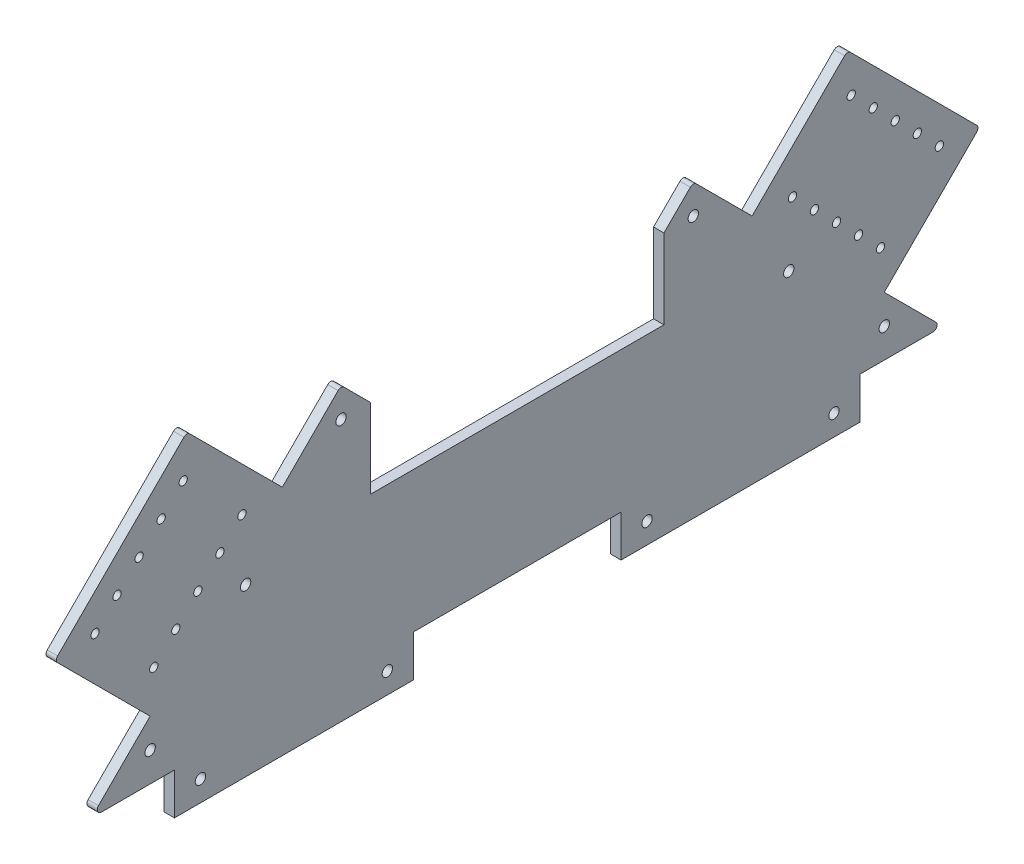
SolidWorks part; units mm, degrees
ref_plane "前视基准面" through (0, 0, 0) normal (0, 0, 1) x (1, 0, 0)
ref_plane "上视基准面" through (0, 0, 0) normal (0, 1, 0) x (1, 0, 0)
ref_plane "右视基准面" through (0, 0, 0) normal (1, 0, 0) x (0, 0, -1)
sketch "草图1" plane through (0, 0, 0) normal (1, 0, 0) x (0, 0, -1)
  line L0 (0, 207.0211) -> (0, -61.86) construction
  line L1 (205, 0) -> (-205, 0)
  line L2 (-205, 0) -> (-176.7157, 28.2843)
  line L4 (205, 0) -> (176.7157, 28.2843)
  line L5 (-84.7918, 120.2082) -> (-70.6497, 106.066)
  line L6 (-70.6497, 106.066) -> (-70.6497, 67.7729)
  line L7 (-70.6497, 67.7729) -> (70.6497, 67.7729)
  line L8 (70.6497, 106.066) -> (70.6497, 67.7729)
  line L9 (84.7918, 120.2082) -> (70.6497, 106.066)
  line L10 (-176.7157, 28.2843) -> (-222.6777, 74.2462)
  line L11 (-222.6777, 74.2462) -> (-159.0381, 137.8858)
  line L12 (-159.0381, 137.8858) -> (-113.0761, 91.9239)
  line L13 (176.7157, 28.2843) -> (222.6777, 74.2462)
  line L14 (222.6777, 74.2462) -> (159.0381, 137.8858)
  line L15 (159.0381, 137.8858) -> (113.0761, 91.9239)
  line L16 (-113.0761, 91.9239) -> (-84.7918, 120.2082)
  line L17 (113.0761, 91.9239) -> (84.7918, 120.2082)
  line L18 (-143.1282, 79.5495) -> (-180.2513, 116.6726) construction
  line L19 (-136.0571, 114.9049) -> (-199.6967, 51.2652) construction
  line L20 (-165, 0) -> (-165, -20)
  line L21 (-165, -20) -> (-50, -20)
  line L22 (-50, -20) -> (-50, 0)
  line L23 (50, -20) -> (50, 0)
  line L24 (165, -20) -> (50, -20)
  line L25 (165, 0) -> (165, -20)
  line L26 (-165, -10) -> (-50, -10) construction
  circle A0 centre (-143.1282, 79.5495) radius 2
  circle A1 centre (-171.4124, 107.8338) radius 2
  circle A2 centre (-153.7348, 68.9429) radius 2
  circle A3 centre (-182.019, 97.2272) radius 2
  circle A8 centre (-164.3414, 58.3363) radius 2
  circle A9 centre (-192.6256, 86.6206) radius 2
  circle A16 centre (-132.5216, 90.1561) radius 2
  circle A17 centre (-160.8058, 118.4404) radius 2
  circle A28 centre (-174.948, 47.7297) radius 2
  circle A29 centre (-203.2322, 76.014) radius 2
  circle A32 centre (132.5216, 90.1561) radius 2
  circle A33 centre (160.8058, 118.4404) radius 2
  circle A34 centre (182.019, 97.2272) radius 2
  circle A35 centre (171.4124, 107.8338) radius 2
  circle A36 centre (143.1282, 79.5495) radius 2
  circle A37 centre (153.7348, 68.9429) radius 2
  circle A38 centre (203.2322, 76.014) radius 2
  circle A39 centre (192.6256, 86.6206) radius 2
  circle A40 centre (164.3414, 58.3363) radius 2
  circle A41 centre (174.948, 47.7297) radius 2
  circle A44 centre (-152.5, -10) radius 2.5
  circle A45 centre (-62.5, -10) radius 2.5
  circle A46 centre (62.5, -10) radius 2.5
  circle A47 centre (152.5, -10) radius 2.5
  circle A48 centre (-176.7157, 14.1421) radius 2.5
  circle A49 centre (-130.7538, 60.1041) radius 2.5
  circle A50 centre (-84.7918, 106.066) radius 2.5
  circle A51 centre (176.7157, 14.1421) radius 2.5
  circle A52 centre (130.7538, 60.1041) radius 2.5
  circle A53 centre (84.7918, 106.066) radius 2.5
  point P9 (0, 120.2082)
  point P10 (0, 0)
  point P12 (0, 67.7729)
  dimension "D7" = 12.5
  dimension "D8" = 4
  dimension "D9" = 40
  dimension "D17" = 5
  dimension "D18" = 5
  dimension "D22" = 5
  dimension "D25" = 10
  dimension "D1" = 45
  dimension "D2" = 410
  dimension "D3" = 170
  dimension "D4" = 20
  dimension "D5" = 65
  dimension "D6" = 130
  dimension "D10" = 40
  dimension "D14" = 100
  dimension "D15" = 40
  dimension "D16" = 100
  dimension "D19" = 90
  dimension "D20" = 12.5
  dimension "D21" = 20
  dimension "D23" = 10
  dimension "D11" = 4
  dimension "D12" = 1
  dimension "D13" = 2
  dimension "D24" = 3
extrude "凸台-拉伸1" add sketch "草图1" along normal blind 5
fillet "圆角1" radius 2 8 edges at (2.5, 120.2082, -84.7918) (2.5, 120.2082, 84.7918) (2.5, 74.2462, -222.6777) (2.5, 137.8858, -159.0381) (2.5, 137.8858, 159.0381) (2.5, 74.2462, 222.6777) (2.5, 0, -205) (2.5, 0, 205)
